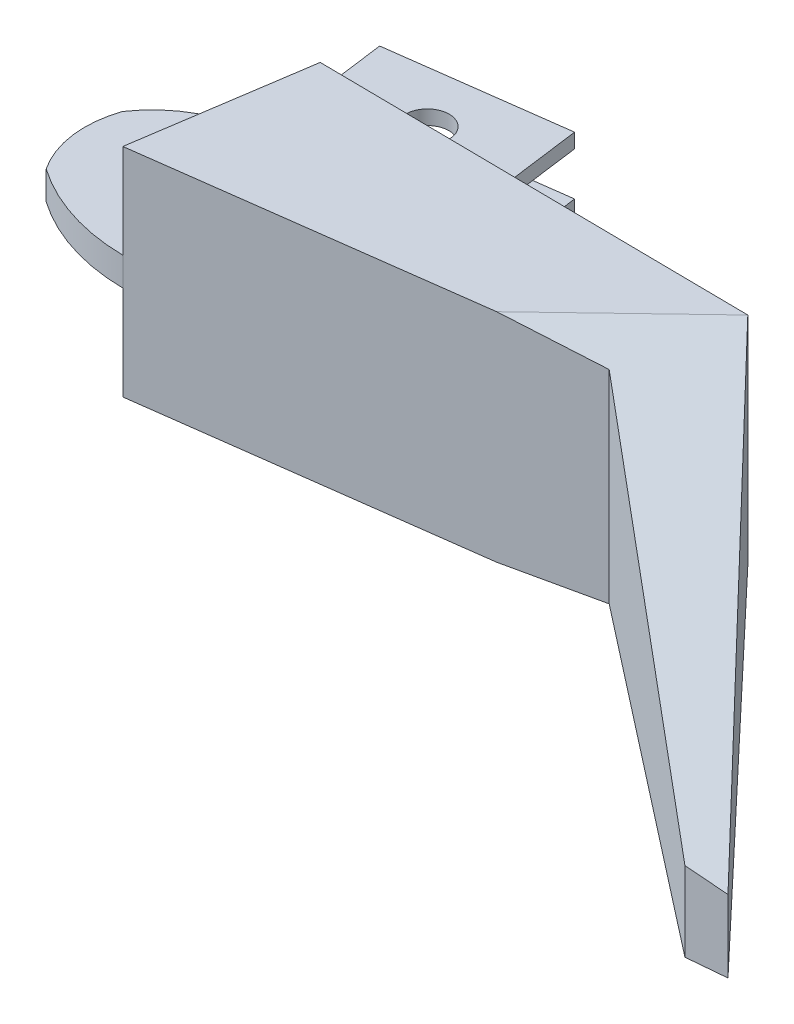
SolidWorks part; units mm, degrees
ref_plane "前视基准面" through (0, 0, 0) normal (0, 0, 1) x (1, 0, 0)
ref_plane "上视基准面" through (0, 0, 0) normal (0, 1, 0) x (1, 0, 0)
ref_plane "右视基准面" through (0, 0, 0) normal (1, 0, 0) x (0, 0, -1)
sketch "草图1" plane through (0, 0, 0) normal (0, 1, 0) x (1, 0, 0)
  line L0 (-296.6252, 119.1829) -> (103.3748, 114.5648)
  line L1 (103.3748, 114.5648) -> (393.4248, -189.1966)
  line L2 (393.4248, -189.1966) -> (363.6612, -189.1966)
  line L3 (363.6612, -189.1966) -> (83.2218, 38.8736)
  line L4 (83.2218, 38.8736) -> (-316.7782, -14.2435)
  line L5 (-296.6252, 119.1829) -> (-316.7782, -14.2435)
  dimension "D1" = 400
  dimension "D2" = 400
  dimension "D3" = 420
extrude "凸台-拉伸1" add sketch "草图1" along normal blind 150
sketch "草图2" plane through (-307.6091, 0, -46.4618) normal (-0.9888, 0, -0.1493) x (-0.1493, 0, 0.9888)
  line L1 (68.9371, 65) -> (-81.0629, 65)
  line L2 (68.9371, 65) -> (68.9371, 85)
  line L3 (68.9371, 85) -> (-81.0629, 85)
  line L4 (-81.0629, 65) -> (-81.0629, 85)
  line L5 (68.9371, 65) -> (-81.0629, 85) construction
  line L6 (68.9371, 85) -> (-81.0629, 65) construction
  point P0 (-6.0629, 75)
  dimension "D1" = 150
  dimension "D2" = 20
  dimension "D3" = 65
sketch "草图3" plane through (-307.6091, 0, -46.4618) normal (-0.9888, 0, -0.1493) x (-0.1493, 0, 0.9888)
  line L0 (-73.546, 150) -> (-124.3579, 150)
  line L1 (-73.546, 150) -> (61.3939, 150)
  line L2 (61.3939, 150) -> (61.3939, 84.9223)
  line L3 (61.3939, 150) -> (61.3939, 0) construction
  line L4 (61.3939, 84.9223) -> (61.3939, 150)
  line L5 (74.2466, 150) -> (74.2466, 84.9223)
  line L6 (74.2466, 84.9223) -> (74.2466, 150)
  line L7 (61.3939, 150) -> (74.2466, 150)
  line L8 (61.3939, 150) -> (74.2466, 150)
  line L9 (74.2466, 84.9223) -> (-108.9706, 84.9223)
  line L10 (-108.9706, 84.9223) -> (-110.2996, 150)
  line L12 (-73.546, 65.2123) -> (-110.2996, 65.2123)
  line L13 (-73.546, 150) -> (-73.546, 0) construction
  line L14 (-110.2996, 65.2123) -> (-110.2996, 0)
  line L15 (-110.2996, 0) -> (83.7196, 0)
  line L16 (83.7196, 0) -> (83.7196, 65.2123)
  line L17 (83.7196, 65.2123) -> (-88.6278, 65.2123)
  line L18 (-88.6278, 65.2123) -> (83.7196, 65.2123)
  line M1 (-73.546, 0) -> (61.3939, 0)
  line M2 (61.3939, 0) -> (61.3939, 150)
  line M3 (61.3939, 150) -> (-73.546, 150)
  line M4 (-73.546, 150) -> (-73.546, 0)
extrude "切除-拉伸5" cut sketch "草图3" against normal blind 100 contours L10 L9 L0 M4 | L9 M2 M3 M4 | L9 L5 L7 M2 | L14 L15 L12 M4 | L17 M2 M4 M1 | L16 L17 L15 M2
sketch "草图4" plane through (0, 84.9223, 0) normal (0, 1, 0) x (1, 0, 0)
  line L0 (-195.667, 118.0174) -> (-296.6252, 119.1829) construction
  line L1 (-317.9047, -21.7022) -> (-295.5026, 126.6155) construction
  circle A0 centre (-255.1935, 58.7006) radius 10
  dimension "D1" = 20
  dimension "D2" = 60
  dimension "D3" = 50
extrude "切除-拉伸6" cut sketch "草图4" against normal blind 100
sketch "草图5" plane through (111.2945, 0, -106.2708) normal (0.7232, 0, -0.6906) x (-0.6906, 0, -0.7232)
  line L0 (11.4679, 150) -> (-408.5321, 100)
  line L1 (-408.5321, 150) -> (-408.5321, 0) construction
  line L2 (11.4679, 0) -> (-408.5321, 50)
  line L3 (-408.5321, 150) -> (11.4679, 150)
  line L4 (-408.5321, 150) -> (-408.5321, 100)
  line L5 (11.4679, 0) -> (-408.5321, 0)
  line L6 (-408.5321, 0) -> (-408.5321, 50)
  dimension "D1" = 50
  dimension "D2" = 50
extrude "切除-拉伸7" cut sketch "草图5" against normal through all contours L4 L0 L3 | L6 L2 L5
sketch "草图9" plane through (-3.6306, 0, -27.3402) normal (0.1316, 0, 0.9913) x (0.9913, 0, -0.1316)
  line L0 (-211.7863, 84.9223) -> (-211.7863, 150) construction
  line L1 (-206.7863, 100) -> (-86.7863, 100)
  line L2 (-206.7863, 100) -> (-206.7863, 50)
  line L3 (-206.7863, 50) -> (-86.7863, 50)
  line L4 (-86.7863, 100) -> (-86.7863, 50)
  line L5 (-206.7863, 100) -> (-86.7863, 50) construction
  line L6 (-206.7863, 50) -> (-86.7863, 100) construction
  line L7 (-211.7863, 150) -> (18.3463, 150) construction
  point P0 (-146.7863, 75)
  dimension "D1" = 120
  dimension "D2" = 50
  dimension "D3" = 5
  dimension "D4" = 50
extrude "凸台-拉伸5" add sketch "草图9" against normal blind 200
sketch "草图12" plane through (-29.9581, 0, -225.5998) normal (-0.1316, 0, -0.9913) x (-0.9913, 0, 0.1316)
  line L1 (83.6516, 90) -> (207.8364, 90)
  line L2 (83.6516, 90) -> (83.6516, 60)
  line L3 (83.6516, 60) -> (207.8364, 60)
  line L4 (207.8364, 90) -> (207.8364, 60)
  line L5 (83.6516, 90) -> (207.8364, 60) construction
  line L6 (83.6516, 60) -> (207.8364, 90) construction
  point P0 (145.744, 75)
  point P5 (146.8605, 74.9986)
  point P6 (144.6574, 74.8247)
  point P8 (145.744, 75)
  dimension "D1" = 30
  dimension "D2" = 10
extrude "切除-拉伸14" cut sketch "草图12" against normal blind 60
sketch "草图13" plane through (0, 50, 0) normal (0, -1, 0) x (-1, 0, 0)
  line L0 (234.9449, 198.379) -> (115.9892, 214.1755) construction
  line L1 (115.9892, 214.1755) -> (103.0781, 116.9484) construction
  circle A0 centre (170.2015, 166.6254) radius 15
  dimension "D1" = 30
  dimension "D2" = 40
  dimension "D3" = 60
extrude "切除-拉伸15" cut sketch "草图13" against normal through all
sketch "草图14" plane through (0, 65.2123, 0) normal (0, -1, 0) x (1, 0, 0)
  line L1 (-317.9047, 21.7022) -> (-295.5026, -126.6155) construction
  line L2 (-316.7782, 14.2435) -> (-213.5739, 0.5387)
  line L3 (-316.7782, 14.2435) -> (-308.7804, -38.7074)
  arc A0 (-213.5739, 0.5387) -> (-308.7804, -38.7074) centre (-211.9815, -138.4271) ccw
extrude "切除-拉伸16" cut sketch "草图14" against normal blind 600
sketch "草图15" plane through (0, 65.2123, 0) normal (0, -1, 0) x (-1, 0, 0)
  line L0 (317.9047, -21.7022) -> (295.5026, 126.6155) construction
  line L1 (302.3731, 81.1278) -> (296.6252, 119.1829)
  line L2 (296.6252, 119.1829) -> (224.3174, 118.3481)
  arc A0 (224.3174, 118.3481) -> (302.3731, 81.1278) centre (235.9504, 42.2875) cw
  line M5 (308.7804, 38.7074) -> (296.6252, 119.1829)
  line M6 (296.6252, 119.1829) -> (224.3174, 118.3481)
extrude "切除-拉伸18" cut sketch "草图15" against normal blind 600 contours A0 M6 M5
sketch "草图16" plane through (0, 65.2123, 0) normal (0, -1, 0) x (-1, 0, 0)
  line L0 (291.6587, 24.5606) -> (320.9797, 36.5817)
  line L1 (320.9797, 36.5817) -> (321.3451, 76.7655)
  line L2 (321.3451, 76.7655) -> (299.7079, 85.3633)
  arc A0 (291.6587, 24.5606) -> (299.7079, 85.3633) centre (234.0934, 63.1154) ccw
  arc A1 (213.5739, -0.5387) -> (308.7804, 38.7074) centre (211.9815, 138.4271) ccw construction
  arc A2 (302.3731, 81.1278) -> (245.8243, 118.5964) centre (235.9504, 42.2875) ccw construction
extrude "切除-拉伸23" cut sketch "草图16" against normal blind 600
